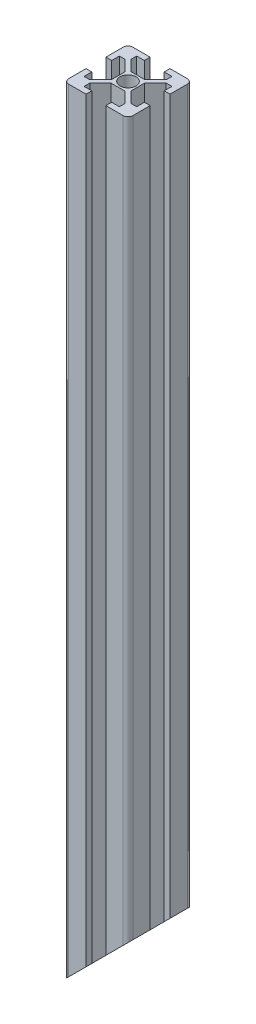
SolidWorks part; units mm, degrees
ref_plane "前视基准面" through (0, 0, 0) normal (0, 0, 1) x (1, 0, 0)
ref_plane "上视基准面" through (0, 0, 0) normal (0, 1, 0) x (1, 0, 0)
ref_plane "右视基准面" through (0, 0, 0) normal (1, 0, 0) x (0, 0, -1)
sketch "草图1" plane through (0, 0, 0) normal (0, 1, 0) x (1, 0, 0)
  line L0 (-218.7193, -330.1484) -> (-216.9193, -330.1484)
  line L1 (-217.2193, -317.0484) -> (-200.2193, -317.0484)
  line L2 (-218.7193, -318.5484) -> (-218.7193, -335.5484)
  line L3 (-217.2193, -337.0484) -> (-200.2193, -337.0484)
  line L4 (-198.7193, -318.5484) -> (-198.7193, -335.5484)
  line L5 (-218.7193, -317.0484) -> (-198.7193, -337.0484) construction
  line L6 (-218.7193, -337.0484) -> (-198.7193, -317.0484) construction
  line L7 (-211.7734, -323.9484) -> (-205.6652, -323.9484)
  line L8 (-211.7734, -323.9484) -> (-211.7734, -330.1484)
  line L9 (-211.7734, -330.1484) -> (-205.6652, -330.1484)
  line L10 (-205.6652, -323.9484) -> (-205.6652, -330.1484)
  line L11 (-211.7734, -323.9484) -> (-205.6652, -330.1484) construction
  line L12 (-211.7734, -330.1484) -> (-205.6652, -323.9484) construction
  line L13 (-216.9193, -330.1484) -> (-216.9193, -332.5484)
  line L14 (-216.9193, -332.5484) -> (-215.1164, -332.5484)
  line L15 (-215.1164, -332.5484) -> (-211.7734, -329.2054)
  line L16 (-214.2193, -320.6513) -> (-210.8764, -323.9942)
  line L17 (-214.2193, -318.8484) -> (-214.2193, -320.6513)
  line L18 (-211.8193, -318.8484) -> (-214.2193, -318.8484)
  line L19 (-211.8193, -317.0484) -> (-211.8193, -318.8484)
  line L20 (-202.3223, -321.5484) -> (-205.6652, -324.8913)
  line L21 (-200.5193, -321.5484) -> (-202.3223, -321.5484)
  line L22 (-200.5193, -323.9484) -> (-200.5193, -321.5484)
  line L23 (-198.7193, -323.9484) -> (-200.5193, -323.9484)
  line L24 (-203.2193, -333.4454) -> (-206.5622, -330.1025)
  line L25 (-203.2193, -335.2484) -> (-203.2193, -333.4454)
  line L26 (-205.6193, -335.2484) -> (-203.2193, -335.2484)
  line L27 (-205.6193, -337.0484) -> (-205.6193, -335.2484)
  line L28 (-211.8193, -337.0484) -> (-211.8193, -335.2484)
  line L29 (-211.8193, -335.2484) -> (-214.2193, -335.2484)
  line L30 (-214.2193, -335.2484) -> (-214.2193, -333.4454)
  line L31 (-214.2193, -333.4454) -> (-210.8764, -330.1025)
  line L32 (-216.9193, -321.5484) -> (-215.1164, -321.5484)
  line L33 (-215.1164, -321.5484) -> (-211.7734, -324.8913)
  line L34 (-216.9193, -323.9484) -> (-216.9193, -321.5484)
  line L35 (-218.7193, -323.9484) -> (-216.9193, -323.9484)
  line L36 (-203.2193, -318.8484) -> (-203.2193, -320.6513)
  line L37 (-203.2193, -320.6513) -> (-206.5622, -323.9942)
  line L38 (-205.6193, -318.8484) -> (-203.2193, -318.8484)
  line L39 (-205.6193, -317.0484) -> (-205.6193, -318.8484)
  line L40 (-200.5193, -332.5484) -> (-202.3223, -332.5484)
  line L41 (-202.3223, -332.5484) -> (-205.6652, -329.2054)
  line L42 (-200.5193, -330.1484) -> (-200.5193, -332.5484)
  line L43 (-198.7193, -330.1484) -> (-200.5193, -330.1484)
  circle A0 centre (-208.7193, -327.0484) radius 2.5
  arc A1 (-218.7193, -318.5484) -> (-217.2193, -317.0484) centre (-217.2193, -318.5484) cw
  arc A2 (-218.7193, -335.5484) -> (-217.2193, -337.0484) centre (-217.2193, -335.5484) ccw
  arc A3 (-200.2193, -317.0484) -> (-198.7193, -318.5484) centre (-200.2193, -318.5484) cw
  arc A4 (-198.7193, -335.5484) -> (-200.2193, -337.0484) centre (-200.2193, -335.5484) cw
  point P0 (-208.7193, -327.0484)
  point P19 (-208.7193, -327.0484)
  point P25 (-208.7193, -327.0484)
  point P31 (-208.7193, -327.0484)
  point P37 (-208.7193, -327.0484)
  point P59 (-208.7193, -327.0484)
extrude "凸台-拉伸1" add sketch "草图1" along normal blind 242.72
sketch "草图2" plane through (0, 0, 337.0484) normal (0, 0, 1) x (1, 0, 0)
  line L0 (-218.7193, 0) -> (-198.7193, 20)
  line L1 (-198.7193, 242.72) -> (-198.7193, 0) construction
  line L2 (-218.7193, 242.72) -> (-218.7193, 0) construction
  line L3 (-198.7193, 20) -> (-198.7193, 0)
  line L4 (-198.7193, 0) -> (-218.7193, 0)
  dimension "D1" = 45
extrude "切除-拉伸1" cut sketch "草图2" against normal through all
